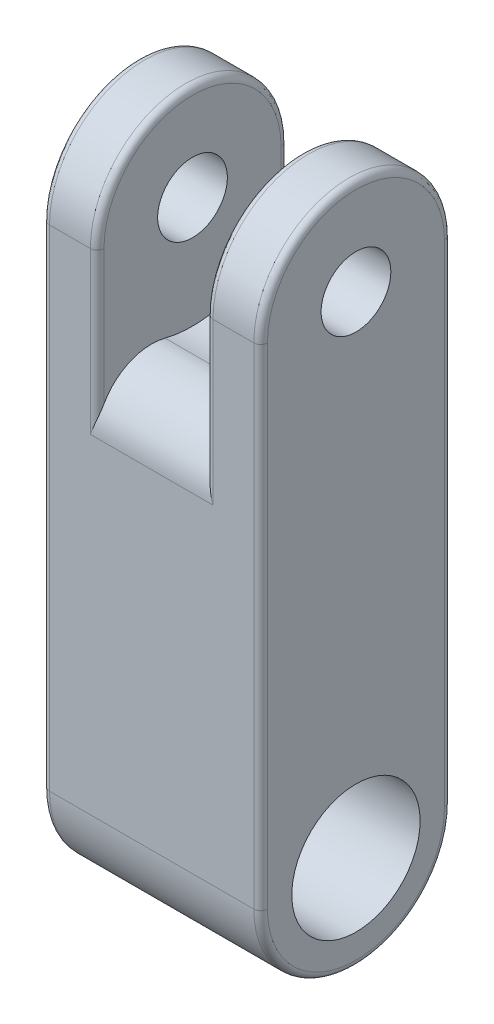
SolidWorks part; units mm, degrees
ref_plane "Front Plane" through (0, 0, 0) normal (0, 0, 1) x (1, 0, 0)
ref_plane "Top Plane" through (0, 0, 0) normal (0, 1, 0) x (1, 0, 0)
ref_plane "Right Plane" through (0, 0, 0) normal (1, 0, 0) x (0, 0, -1)
sketch "Sketch1" plane through (0, 0, 0) normal (1, 0, 0) x (0, 0, -1)
  line L0 (-5.5562, 0) -> (-5.5562, 28.575)
  line L1 (5.5562, 28.575) -> (5.5563, 0)
  line L3 (3.7395, 0) -> (1.8697, 3.2385) construction
  line L4 (1.8697, 3.2385) -> (-1.8697, 3.2385) construction
  line L5 (-1.8697, 3.2385) -> (-3.7395, 0) construction
  line L6 (-3.7395, 0) -> (-1.8697, -3.2385) construction
  line L7 (-1.8697, -3.2385) -> (1.8697, -3.2385) construction
  line L8 (1.8697, -3.2385) -> (3.7395, 0) construction
  arc A0 (-5.5562, 0) -> (5.5563, 0) centre (0, 0) ccw
  arc A1 (-5.5562, 28.575) -> (5.5562, 28.575) centre (0, 28.575) cw
  circle A2 centre (0, 0) radius 3.7395
  circle A3 centre (0, 28.575) radius 2.032
  circle A4 centre (0, 0) radius 3.2385 construction
  dimension "D1" = 5.5562
  dimension "D2" = 6.477
  dimension "D4" = 4.064
  dimension "D3" = 28.575
extrude "Boss-Extrude1" add sketch "Sketch1" along normal mid plane 12.7
sketch "Sketch2" plane through (0, 0, 0) normal (1, 0, 0) x (0, 0, -1)
  circle A0 centre (0, 28.575) radius 6.5
  dimension "D1" = 13
extrude "Cut-Extrude1" cut sketch "Sketch2" against normal mid plane 6.35
fillet "Fillet1" radius 3.175 2 edges at (0, 25.2019, 5.5562) (0, 25.2019, -5.5562)
fillet "Fillet2" radius 0.3969 14 edges at (6.35, 14.2875, -5.5563) (6.35, -5.5562, 0) (6.35, 14.2875, 5.5562) (-6.35, 14.2875, -5.5563) (-6.35, -5.5562, 0) (-6.35, 14.2875, 5.5562) (6.35, 34.1313, 0) (-6.35, 34.1313, 0) (-3.175, 23.8863, -5.5562) (-3.175, 23.8863, 5.5562) (3.175, 23.8863, -5.5562) (3.175, 23.8863, 5.5562) (-3.175, 34.1313, 0) (3.175, 34.1313, 0)
